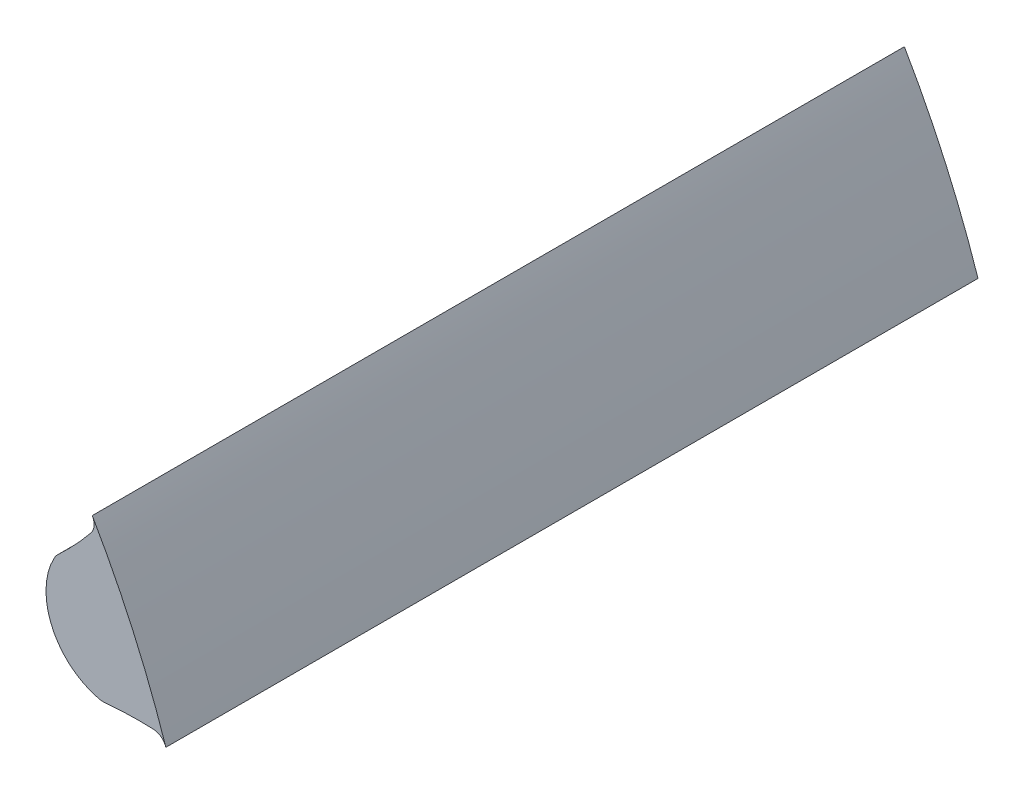
SolidWorks part; units mm, degrees
ref_plane "Front Plane" through (0, 0, 0) normal (0, 0, 1) x (1, 0, 0)
ref_plane "Top Plane" through (0, 0, 0) normal (0, 1, 0) x (1, 0, 0)
ref_plane "Right Plane" through (0, 0, 0) normal (1, 0, 0) x (0, 0, -1)
sketch "Sketch1" plane through (0, 0, 0) normal (0, 0, 1) x (1, 0, 0)
  arc A7 (48.8586, -1.179) -> (48.3981, -0.8311) centre (48.3763, -1.3387) ccw
  arc A8 (48.3981, -0.8311) -> (46.6255, -0.8765) centre (47.8425, -13.7732) ccw
  arc A9 (46.3754, -0.8587) -> (46.6255, -0.8765) centre (46.5539, -0.1179) ccw
  arc A10 (44.7293, 2.8058) -> (46.3754, -0.8587) centre (46.9705, 1.6106) ccw
  arc A11 (44.8821, 3.0046) -> (44.7293, 2.8058) centre (45.4016, 2.4472) ccw
  arc A12 (46.0933, 4.2996) -> (46.1391, 4.8749) centre (45.6994, 4.6204) ccw
  arc A13 (44.8821, 3.0046) -> (46.0933, 4.2996) centre (36.0492, 12.4802) ccw
  arc A14 (46.1391, 4.8749) -> (48.8586, -1.179) centre (18.0553, -11.3785) cw
extrude "Boss-Extrude1" add sketch "Sketch1" along normal blind 30
